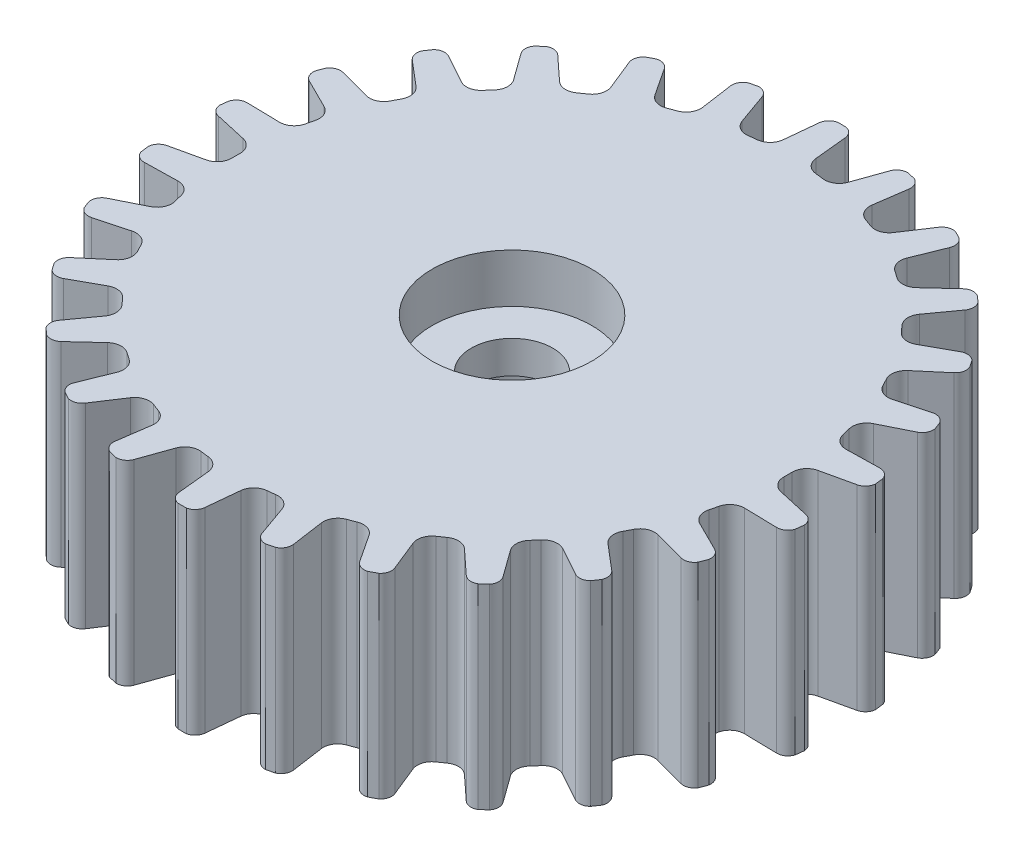
SolidWorks part; units mm, degrees
ref_plane "Front Plane" through (0, 0, 0) normal (0, 0, 1) x (1, 0, 0)
ref_plane "Top Plane" through (0, 0, 0) normal (0, 1, 0) x (1, 0, 0)
ref_plane "Right Plane" through (0, 0, 0) normal (1, 0, 0) x (0, 0, -1)
sketch "Sketch1" plane through (0, 0, 0) normal (0, 1, 0) x (1, 0, 0)
  circle A0 centre (0, 0) radius 2.45
  circle A1 centre (0, 0) radius 10.125
  dimension "D1" = 4.9
  dimension "D2" = 20.25
extrude "Boss-Extrude1" add sketch "Sketch1" along normal blind 6
sketch "Sketch2" plane through (0, 6, 0) normal (0, 1, 0) x (1, 0, 0)
  line L0 (0, 0) -> (0, 10.7871) construction
  line L1 (0.5, 8.825) -> (0.4, 9.825)
  line L2 (-0.5, 8.825) -> (-0.4, 9.825)
  line L3 (1.6265, 8.6882) -> (1.9629, 9.6352)
  line L4 (2.5974, 8.4489) -> (2.7397, 9.4438)
  line L5 (3.6585, 8.0465) -> (4.2117, 8.8855)
  line L6 (4.5439, 7.5818) -> (4.9201, 8.5137)
  line L7 (5.4778, 6.9372) -> (6.2158, 7.6194)
  line L8 (6.2263, 6.274) -> (6.8146, 7.0889)
  line L9 (6.9788, 5.4247) -> (7.8586, 5.9104)
  line L10 (7.5469, 4.6017) -> (8.313, 5.252)
  line L11 (8.0742, 3.5969) -> (9.0447, 3.858)
  line L12 (8.4288, 2.6619) -> (9.3284, 3.11)
  line L13 (8.7004, 1.5601) -> (9.7052, 1.5814)
  line L14 (8.8209, 0.5674) -> (9.8016, 0.7872)
  line L15 (8.8209, -0.5674) -> (9.8016, -0.7872)
  line L16 (8.7004, -1.5601) -> (9.7052, -1.5814)
  line L17 (8.4288, -2.6619) -> (9.3284, -3.11)
  line L18 (8.0742, -3.5969) -> (9.0447, -3.858)
  line L19 (7.5469, -4.6017) -> (8.313, -5.252)
  line L20 (6.9788, -5.4247) -> (7.8586, -5.9104)
  line L21 (6.2263, -6.274) -> (6.8146, -7.0889)
  line L22 (5.4778, -6.9372) -> (6.2158, -7.6194)
  line L23 (4.5439, -7.5818) -> (4.9201, -8.5137)
  line L24 (3.6585, -8.0465) -> (4.2117, -8.8855)
  line L25 (2.5974, -8.4489) -> (2.7397, -9.4438)
  line L26 (1.6265, -8.6882) -> (1.9629, -9.6352)
  line L27 (0.5, -8.825) -> (0.4, -9.825)
  line L28 (-0.5, -8.825) -> (-0.4, -9.825)
  line L29 (-1.6265, -8.6882) -> (-1.9629, -9.6352)
  line L30 (-2.5974, -8.4489) -> (-2.7397, -9.4438)
  line L31 (-3.6585, -8.0465) -> (-4.2117, -8.8855)
  line L32 (-4.5439, -7.5818) -> (-4.9201, -8.5137)
  line L33 (-5.4778, -6.9372) -> (-6.2158, -7.6194)
  line L34 (-6.2263, -6.274) -> (-6.8146, -7.0889)
  line L35 (-6.9788, -5.4247) -> (-7.8586, -5.9104)
  line L36 (-7.5469, -4.6017) -> (-8.313, -5.252)
  line L37 (-8.0742, -3.5969) -> (-9.0447, -3.858)
  line L38 (-8.4288, -2.6619) -> (-9.3284, -3.11)
  line L39 (-8.7004, -1.5601) -> (-9.7052, -1.5814)
  line L40 (-8.8209, -0.5674) -> (-9.8016, -0.7872)
  line L41 (-8.8209, 0.5674) -> (-9.8016, 0.7872)
  line L42 (-8.7004, 1.5601) -> (-9.7052, 1.5814)
  line L43 (-8.4288, 2.6619) -> (-9.3284, 3.11)
  line L44 (-8.0742, 3.5969) -> (-9.0447, 3.858)
  line L45 (-7.5469, 4.6017) -> (-8.313, 5.252)
  line L46 (-6.9788, 5.4247) -> (-7.8586, 5.9104)
  line L47 (-6.2263, 6.274) -> (-6.8146, 7.0889)
  line L48 (-5.4778, 6.9372) -> (-6.2158, 7.6194)
  line L49 (-4.5439, 7.5818) -> (-4.9201, 8.5137)
  line L50 (-3.6585, 8.0465) -> (-4.2117, 8.8855)
  line L51 (-2.5974, 8.4489) -> (-2.7397, 9.4438)
  line L52 (-1.6265, 8.6882) -> (-1.9629, 9.6352)
  circle A0 centre (0, 0) radius 10.125 construction
  circle A1 centre (0, 0) radius 10.125 construction
  arc A2 (0.9, 8.425) -> (1.1424, 8.3956) centre (0, 0) cw
  arc A3 (0.5, 8.825) -> (0.9, 8.425) centre (0.9444, 8.8694) ccw
  arc A4 (0, 10.125) -> (0.4, 9.825) centre (0.0622, 9.7912) cw
  arc A5 (-0.5, 8.825) -> (-0.9, 8.425) centre (-0.9444, 8.8694) cw
  arc A6 (0, 10.125) -> (-0.4, 9.825) centre (-0.0622, 9.7912) ccw
  arc A7 (1.6265, 8.6882) -> (1.1424, 8.3956) centre (1.2056, 8.8377) cw
  arc A8 (2.4231, 9.8308) -> (1.9629, 9.6352) centre (2.2828, 9.5216) ccw
  arc A9 (2.4231, 9.8308) -> (2.7397, 9.4438) centre (2.4035, 9.4918) cw
  arc A10 (2.5974, 8.4489) -> (2.8901, 7.9648) centre (3.0396, 8.3857) ccw
  arc A11 (2.8901, 7.9648) -> (3.1184, 7.8782) centre (0, 0) cw
  arc A12 (3.6585, 8.0465) -> (3.1184, 7.8782) centre (3.2856, 8.2924) cw
  arc A13 (4.7053, 8.9652) -> (4.2117, 8.8855) centre (4.4952, 8.6986) ccw
  arc A14 (4.7053, 8.9652) -> (4.9201, 8.5137) centre (4.6052, 8.6408) cw
  arc A15 (4.5439, 7.5818) -> (4.7122, 7.0417) centre (4.9581, 7.4146) ccw
  arc A16 (4.7122, 7.0417) -> (4.9131, 6.903) centre (0, 0) cw
  arc A17 (5.4778, 6.9372) -> (4.9131, 6.903) centre (5.1746, 7.2652) cw
  arc A18 (6.7141, 7.5787) -> (6.2158, 7.6194) centre (6.4462, 7.3701) ccw
  arc A19 (6.7141, 7.5787) -> (6.8146, 7.0889) centre (6.5393, 7.2876) cw
  arc A20 (6.2263, 6.274) -> (6.2605, 5.7094) centre (6.5885, 6.0126) ccw
  arc A21 (6.2605, 5.7094) -> (6.4224, 5.5266) centre (0, 0) cw
  arc A22 (6.9788, 5.4247) -> (6.4224, 5.5266) centre (6.7629, 5.8157) cw
  arc A23 (8.3327, 5.7517) -> (7.8586, 5.9104) centre (8.0227, 5.6132) ccw
  arc A24 (8.3327, 5.7517) -> (8.313, 5.252) centre (8.0933, 5.5109) cw
  arc A25 (7.5469, 4.6017) -> (7.4449, 4.0453) centre (7.8359, 4.2612) ccw
  arc A26 (7.4449, 4.0453) -> (7.5584, 3.8291) centre (0, 0) cw
  arc A27 (8.0742, 3.5969) -> (7.5584, 3.8291) centre (7.9582, 4.0282) cw
  arc A28 (9.467, 3.5904) -> (9.0447, 3.858) centre (9.1329, 3.5301) ccw
  arc A29 (9.467, 3.5904) -> (9.3284, 3.11) centre (9.177, 3.4139) cw
  arc A30 (8.4288, 2.6619) -> (8.1967, 2.146) centre (8.628, 2.2621) ccw
  arc A31 (8.1967, 2.146) -> (8.2551, 1.909) centre (0, 0) cw
  arc A32 (8.7004, 1.5601) -> (8.2551, 1.909) centre (8.6909, 2.0067) cw
  arc A33 (10.0512, 1.2204) -> (9.7052, 1.5814) centre (9.7123, 1.2419) ccw
  arc A34 (10.0512, 1.2204) -> (9.8016, 0.7872) centre (9.7273, 1.1185) cw
  arc A35 (8.8209, 0.5674) -> (8.4721, 0.1221) centre (8.9186, 0.1315) ccw
  arc A36 (8.4721, 0.1221) -> (8.4721, -0.1221) centre (0, 0) cw
  arc A37 (8.8209, -0.5674) -> (8.4721, -0.1221) centre (8.9186, -0.1315) cw
  arc A38 (10.0512, -1.2204) -> (9.8016, -0.7872) centre (9.7273, -1.1185) ccw
  arc A39 (10.0512, -1.2204) -> (9.7052, -1.5814) centre (9.7123, -1.2419) cw
  arc A40 (8.7004, -1.5601) -> (8.2551, -1.909) centre (8.6909, -2.0067) ccw
  arc A41 (8.2551, -1.909) -> (8.1967, -2.146) centre (0, 0) cw
  arc A42 (8.4288, -2.6619) -> (8.1967, -2.146) centre (8.628, -2.2621) cw
  arc A43 (9.467, -3.5904) -> (9.3284, -3.11) centre (9.177, -3.4139) ccw
  arc A44 (9.467, -3.5904) -> (9.0447, -3.858) centre (9.1329, -3.5301) cw
  arc A45 (8.0742, -3.5969) -> (7.5584, -3.8291) centre (7.9582, -4.0282) ccw
  arc A46 (7.5584, -3.8291) -> (7.4449, -4.0453) centre (0, 0) cw
  arc A47 (7.5469, -4.6017) -> (7.4449, -4.0453) centre (7.8359, -4.2612) cw
  arc A48 (8.3327, -5.7517) -> (8.313, -5.252) centre (8.0933, -5.5109) ccw
  arc A49 (8.3327, -5.7517) -> (7.8586, -5.9104) centre (8.0227, -5.6132) cw
  arc A50 (6.9788, -5.4247) -> (6.4224, -5.5266) centre (6.7629, -5.8157) ccw
  arc A51 (6.4224, -5.5266) -> (6.2605, -5.7094) centre (0, 0) cw
  arc A52 (6.2263, -6.274) -> (6.2605, -5.7094) centre (6.5885, -6.0126) cw
  arc A53 (6.7141, -7.5787) -> (6.8146, -7.0889) centre (6.5393, -7.2876) ccw
  arc A54 (6.7141, -7.5787) -> (6.2158, -7.6194) centre (6.4462, -7.3701) cw
  arc A55 (5.4778, -6.9372) -> (4.9131, -6.903) centre (5.1746, -7.2652) ccw
  arc A56 (4.9131, -6.903) -> (4.7122, -7.0417) centre (0, 0) cw
  arc A57 (4.5439, -7.5818) -> (4.7122, -7.0417) centre (4.9581, -7.4146) cw
  arc A58 (4.7053, -8.9652) -> (4.9201, -8.5137) centre (4.6052, -8.6408) ccw
  arc A59 (4.7053, -8.9652) -> (4.2117, -8.8855) centre (4.4952, -8.6986) cw
  arc A60 (3.6585, -8.0465) -> (3.1184, -7.8782) centre (3.2856, -8.2924) ccw
  arc A61 (3.1184, -7.8782) -> (2.8901, -7.9648) centre (0, 0) cw
  arc A62 (2.5974, -8.4489) -> (2.8901, -7.9648) centre (3.0396, -8.3857) cw
  arc A63 (2.4231, -9.8308) -> (2.7397, -9.4438) centre (2.4035, -9.4918) ccw
  arc A64 (2.4231, -9.8308) -> (1.9629, -9.6352) centre (2.2828, -9.5216) cw
  arc A65 (1.6265, -8.6882) -> (1.1424, -8.3956) centre (1.2056, -8.8377) ccw
  arc A66 (1.1424, -8.3956) -> (0.9, -8.425) centre (0, 0) cw
  arc A67 (0.5, -8.825) -> (0.9, -8.425) centre (0.9444, -8.8694) cw
  arc A68 (0, -10.125) -> (0.4, -9.825) centre (0.0622, -9.7912) ccw
  arc A69 (0, -10.125) -> (-0.4, -9.825) centre (-0.0622, -9.7912) cw
  arc A70 (-0.5, -8.825) -> (-0.9, -8.425) centre (-0.9444, -8.8694) ccw
  arc A71 (-0.9, -8.425) -> (-1.1424, -8.3956) centre (0, 0) cw
  arc A72 (-1.6265, -8.6882) -> (-1.1424, -8.3956) centre (-1.2056, -8.8377) cw
  arc A73 (-2.4231, -9.8308) -> (-1.9629, -9.6352) centre (-2.2828, -9.5216) ccw
  arc A74 (-2.4231, -9.8308) -> (-2.7397, -9.4438) centre (-2.4035, -9.4918) cw
  arc A75 (-2.5974, -8.4489) -> (-2.8901, -7.9648) centre (-3.0396, -8.3857) ccw
  arc A76 (-2.8901, -7.9648) -> (-3.1184, -7.8782) centre (0, 0) cw
  arc A77 (-3.6585, -8.0465) -> (-3.1184, -7.8782) centre (-3.2856, -8.2924) cw
  arc A78 (-4.7053, -8.9652) -> (-4.2117, -8.8855) centre (-4.4952, -8.6986) ccw
  arc A79 (-4.7053, -8.9652) -> (-4.9201, -8.5137) centre (-4.6052, -8.6408) cw
  arc A80 (-4.5439, -7.5818) -> (-4.7122, -7.0417) centre (-4.9581, -7.4146) ccw
  arc A81 (-4.7122, -7.0417) -> (-4.9131, -6.903) centre (0, 0) cw
  arc A82 (-5.4778, -6.9372) -> (-4.9131, -6.903) centre (-5.1746, -7.2652) cw
  arc A83 (-6.7141, -7.5787) -> (-6.2158, -7.6194) centre (-6.4462, -7.3701) ccw
  arc A84 (-6.7141, -7.5787) -> (-6.8146, -7.0889) centre (-6.5393, -7.2876) cw
  arc A85 (-6.2263, -6.274) -> (-6.2605, -5.7094) centre (-6.5885, -6.0126) ccw
  arc A86 (-6.2605, -5.7094) -> (-6.4224, -5.5266) centre (0, 0) cw
  arc A87 (-6.9788, -5.4247) -> (-6.4224, -5.5266) centre (-6.7629, -5.8157) cw
  arc A88 (-8.3327, -5.7517) -> (-7.8586, -5.9104) centre (-8.0227, -5.6132) ccw
  arc A89 (-8.3327, -5.7517) -> (-8.313, -5.252) centre (-8.0933, -5.5109) cw
  arc A90 (-7.5469, -4.6017) -> (-7.4449, -4.0453) centre (-7.8359, -4.2612) ccw
  arc A91 (-7.4449, -4.0453) -> (-7.5584, -3.8291) centre (0, 0) cw
  arc A92 (-8.0742, -3.5969) -> (-7.5584, -3.8291) centre (-7.9582, -4.0282) cw
  arc A93 (-9.467, -3.5904) -> (-9.0447, -3.858) centre (-9.1329, -3.5301) ccw
  arc A94 (-9.467, -3.5904) -> (-9.3284, -3.11) centre (-9.177, -3.4139) cw
  arc A95 (-8.4288, -2.6619) -> (-8.1967, -2.146) centre (-8.628, -2.2621) ccw
  arc A96 (-8.1967, -2.146) -> (-8.2551, -1.909) centre (0, 0) cw
  arc A97 (-8.7004, -1.5601) -> (-8.2551, -1.909) centre (-8.6909, -2.0067) cw
  arc A98 (-10.0512, -1.2204) -> (-9.7052, -1.5814) centre (-9.7123, -1.2419) ccw
  arc A99 (-10.0512, -1.2204) -> (-9.8016, -0.7872) centre (-9.7273, -1.1185) cw
  arc A100 (-8.8209, -0.5674) -> (-8.4721, -0.1221) centre (-8.9186, -0.1315) ccw
  arc A101 (-8.4721, -0.1221) -> (-8.4721, 0.1221) centre (0, 0) cw
  arc A102 (-8.8209, 0.5674) -> (-8.4721, 0.1221) centre (-8.9186, 0.1315) cw
  arc A103 (-10.0512, 1.2204) -> (-9.8016, 0.7872) centre (-9.7273, 1.1185) ccw
  arc A104 (-10.0512, 1.2204) -> (-9.7052, 1.5814) centre (-9.7123, 1.2419) cw
  arc A105 (-8.7004, 1.5601) -> (-8.2551, 1.909) centre (-8.6909, 2.0067) ccw
  arc A106 (-8.2551, 1.909) -> (-8.1967, 2.146) centre (0, 0) cw
  arc A107 (-8.4288, 2.6619) -> (-8.1967, 2.146) centre (-8.628, 2.2621) cw
  arc A108 (-9.467, 3.5904) -> (-9.3284, 3.11) centre (-9.177, 3.4139) ccw
  arc A109 (-9.467, 3.5904) -> (-9.0447, 3.858) centre (-9.1329, 3.5301) cw
  arc A110 (-8.0742, 3.5969) -> (-7.5584, 3.8291) centre (-7.9582, 4.0282) ccw
  arc A111 (-7.5584, 3.8291) -> (-7.4449, 4.0453) centre (0, 0) cw
  arc A112 (-7.5469, 4.6017) -> (-7.4449, 4.0453) centre (-7.8359, 4.2612) cw
  arc A113 (-8.3327, 5.7517) -> (-8.313, 5.252) centre (-8.0933, 5.5109) ccw
  arc A114 (-8.3327, 5.7517) -> (-7.8586, 5.9104) centre (-8.0227, 5.6132) cw
  arc A115 (-6.9788, 5.4247) -> (-6.4224, 5.5266) centre (-6.7629, 5.8157) ccw
  arc A116 (-6.4224, 5.5266) -> (-6.2605, 5.7094) centre (0, 0) cw
  arc A117 (-6.2263, 6.274) -> (-6.2605, 5.7094) centre (-6.5885, 6.0126) cw
  arc A118 (-6.7141, 7.5787) -> (-6.8146, 7.0889) centre (-6.5393, 7.2876) ccw
  arc A119 (-6.7141, 7.5787) -> (-6.2158, 7.6194) centre (-6.4462, 7.3701) cw
  arc A120 (-5.4778, 6.9372) -> (-4.9131, 6.903) centre (-5.1746, 7.2652) ccw
  arc A121 (-4.9131, 6.903) -> (-4.7122, 7.0417) centre (0, 0) cw
  arc A122 (-4.5439, 7.5818) -> (-4.7122, 7.0417) centre (-4.9581, 7.4146) cw
  arc A123 (-4.7053, 8.9652) -> (-4.9201, 8.5137) centre (-4.6052, 8.6408) ccw
  arc A124 (-4.7053, 8.9652) -> (-4.2117, 8.8855) centre (-4.4952, 8.6986) cw
  arc A125 (-3.6585, 8.0465) -> (-3.1184, 7.8782) centre (-3.2856, 8.2924) ccw
  arc A126 (-3.1184, 7.8782) -> (-2.8901, 7.9648) centre (0, 0) cw
  arc A127 (-2.5974, 8.4489) -> (-2.8901, 7.9648) centre (-3.0396, 8.3857) cw
  arc A128 (-2.4231, 9.8308) -> (-2.7397, 9.4438) centre (-2.4035, 9.4918) ccw
  arc A129 (-2.4231, 9.8308) -> (-1.9629, 9.6352) centre (-2.2828, 9.5216) cw
  arc A130 (-1.6265, 8.6882) -> (-1.1424, 8.3956) centre (-1.2056, 8.8377) ccw
  arc A131 (-1.1424, 8.3956) -> (-0.9, 8.425) centre (0, 0) cw
  circle A132 centre (0, 0) radius 11.1781
  point P321 (0, 0)
  dimension "D7" = 26
  dimension "D1" = 0.4
  dimension "D2" = 0.1
  dimension "D3" = 1
  dimension "D4" = 0.3
  dimension "D5" = 0.4
  dimension "D6" = 0.4
extrude "Cut-Extrude1" cut sketch "Sketch2" against normal up to next
sketch "Sketch3" plane through (0, 6, 0) normal (0, 1, 0) x (1, 0, 0)
  circle A0 centre (0, 0) radius 2.45 construction
  circle A1 centre (0, 0) radius 2.45
  circle A2 centre (0, 0) radius 1.25
  dimension "D1" = 2.5
extrude "Boss-Extrude2" add sketch "Sketch3" against normal blind 2.5
sketch "Sketch4" plane through (0, 6, 0) normal (0, 1, 0) x (1, 0, 0)
  circle A0 centre (0, 0) radius 2.45
  circle A1 centre (0, 0) radius 2.45 construction
extrude "Cut-Extrude2" cut sketch "Sketch4" against normal blind 1.5
